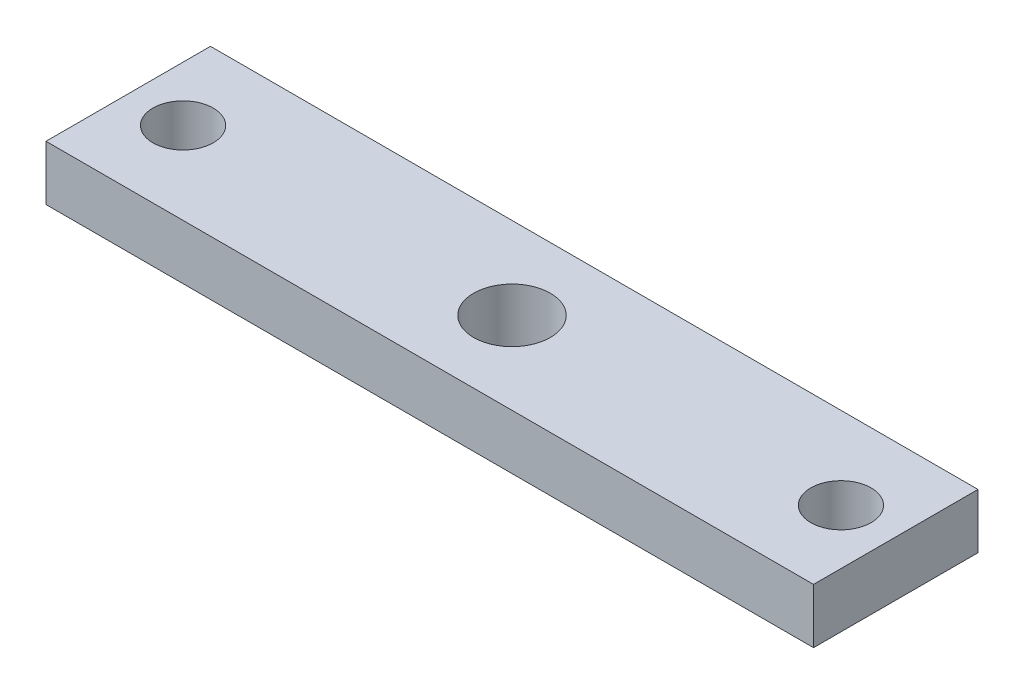
SolidWorks part; units mm, degrees
material "Alloy Steel"
ref_plane "Front Plane" through (0, 0, 0) normal (0, 0, 1) x (1, 0, 0)
ref_plane "Top Plane" through (0, 0, 0) normal (0, 1, 0) x (1, 0, 0)
ref_plane "Right Plane" through (0, 0, 0) normal (1, 0, 0) x (0, 0, -1)
sketch "Sketch1" plane through (0, 0, 0) normal (0, 1, 0) x (1, 0, 0)
  line L1 (-70, 15) -> (70, 15)
  line L2 (-70, 15) -> (-70, -15)
  line L3 (-70, -15) -> (70, -15)
  line L4 (70, 15) -> (70, -15)
  line L5 (-70, 15) -> (70, -15) construction
  line L6 (-70, -15) -> (70, 15) construction
  point P0 (0, 0)
  dimension "D1" = 140
  dimension "D2" = 30
extrude "Boss-Extrude1" add sketch "Sketch1" along normal blind 10
sketch "Sketch2" plane through (0, 10, 0) normal (0, 1, 0) x (1, 0, 0)
  line L0 (-5.5, 0) -> (5.5, 0) construction
  circle A0 centre (-60, 0) radius 5.5
  circle A1 centre (60, 0) radius 5.5
  dimension "D1" = 11
  dimension "D2" = 60
  dimension "D3" = 120
extrude "Cut-Extrude1" cut sketch "Sketch2" against normal through all
sketch "Sketch3" plane through (0, 10, 0) normal (0, 1, 0) x (1, 0, 0)
  point P0 (0, 0)
hole_wizard "M16 Tapped Hole1" positions "3DSketch1" profile "Sketch4" tap size "M16" standard "ISO"
sketch3d "3DSketch1"
  point P0 (0, 0, 0)
  point P3 (0, 0, 0)
  point P5 (0, 10, 0)
sketch "Sketch4" plane through (0, 10, 0) normal (1, 0, 0) x (0, 0, 1)
  line L0 (0, 0) -> (0, 45)
  line L1 (0, 45) -> (7, 38)
  line L2 (7, 38) -> (7, 0)
  line L5 (7, 0) -> (0, 0)
  line L10 (0, 45) -> (-7, 38) construction
  line L11 (0, -6.35) -> (0, 107.95) construction
  dimension "Tap Drill Dia." = 14
  dimension "Tap Drill Depth" = 38
  dimension "Drill Angle" = 90
cosmetic thread "Hole Thread1" parameters "D1"=32, "D2"=16
cosmetic thread "Hole Thread2" parameters "D1"=32, "D2"=16
cosmetic thread "Hole Thread3" parameters "D1"=32, "D2"=16
